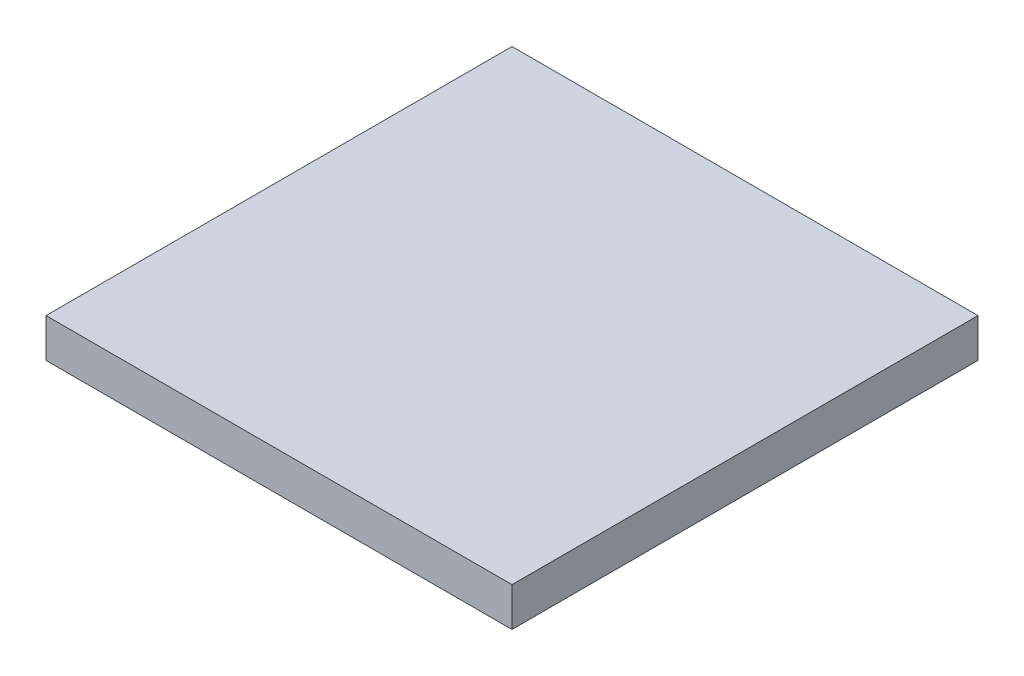
SolidWorks part; units mm, degrees
material "Polyurethane Foam Rigid"
ref_plane "Front Plane" through (0, 0, 0) normal (0, 0, 1) x (1, 0, 0)
ref_plane "Top Plane" through (0, 0, 0) normal (0, 1, 0) x (1, 0, 0)
ref_plane "Right Plane" through (0, 0, 0) normal (1, 0, 0) x (0, 0, -1)
sketch "Sketch1" plane through (0, 0, 0) normal (0, 1, 0) x (1, 0, 0)
  line L1 (-38.1, -38.1) -> (38.1, -38.1)
  line L2 (-38.1, -38.1) -> (-38.1, 38.1)
  line L3 (-38.1, 38.1) -> (38.1, 38.1)
  line L4 (38.1, -38.1) -> (38.1, 38.1)
  line L5 (-38.1, -38.1) -> (38.1, 38.1) construction
  line L6 (-38.1, 38.1) -> (38.1, -38.1) construction
  point P0 (0, 0)
  dimension "D1" = 76.2
  dimension "D2" = 76.2
extrude "Boss-Extrude1" add sketch "Sketch1" along normal blind 6.35
